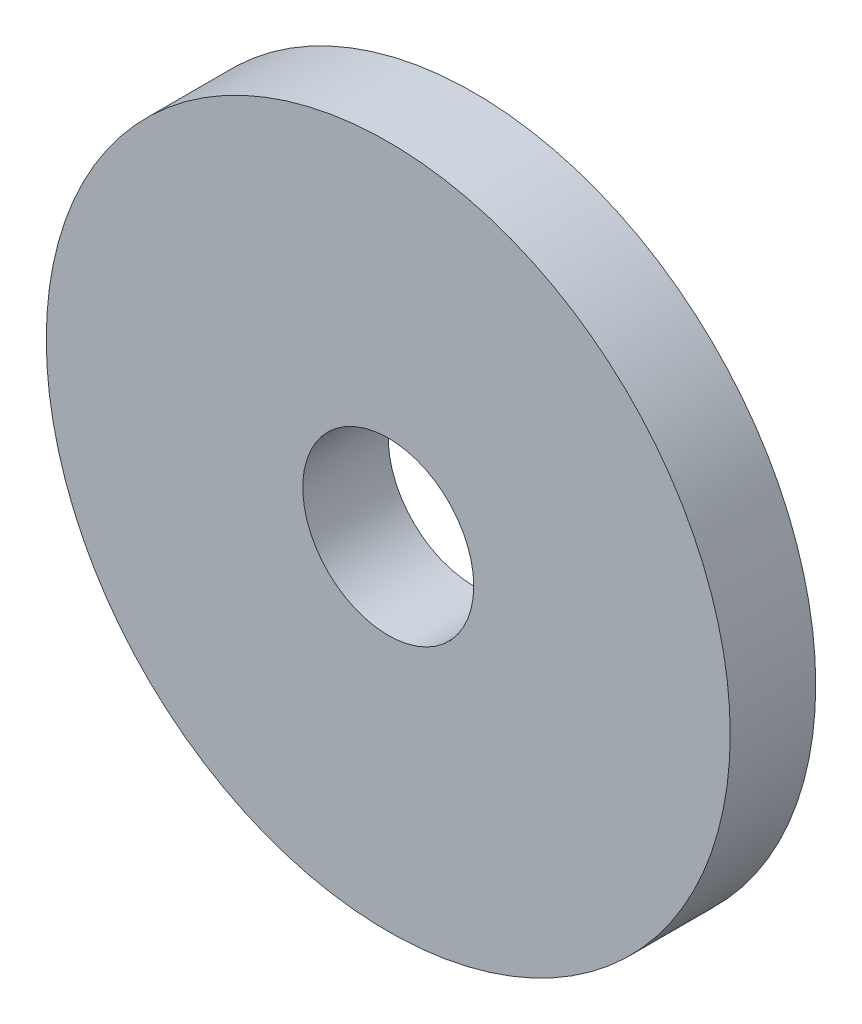
SolidWorks part; units mm, degrees
material "MC ナイロン"
ref_plane "正面" through (0, 0, 0) normal (0, 0, 1) x (1, 0, 0)
ref_plane "平面" through (0, 0, 0) normal (0, 1, 0) x (1, 0, 0)
ref_plane "右側面" through (0, 0, 0) normal (1, 0, 0) x (0, 0, -1)
sketch "ｽｹｯﾁ1" plane through (0, 0, 0) normal (0, 0, 1) x (1, 0, 0)
  circle A0 centre (0, 0) radius 20
  dimension "D1" = 40
extrude "ﾎﾞｽ - 押し出し1" add sketch "ｽｹｯﾁ1" along normal blind 5
sketch "ｽｹｯﾁ2" plane through (0, 0, 5) normal (0, 0, 1) x (1, 0, 0)
  circle A0 centre (0, 0) radius 5
  dimension "D1" = 10
extrude "ｶｯﾄ - 押し出し1" cut sketch "ｽｹｯﾁ2" against normal up to surface (5 mm away) up to face at (20, 0, 0)
